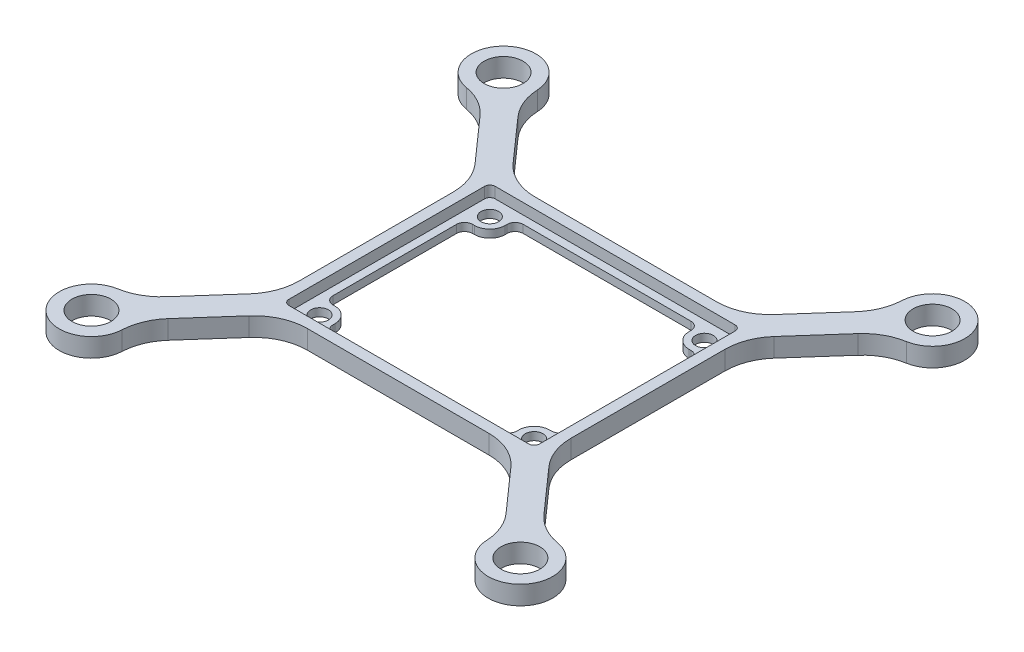
SolidWorks part; units mm, degrees
ref_plane "Front Plane" through (0, 0, 0) normal (0, 0, 1) x (1, 0, 0)
ref_plane "Top Plane" through (0, 0, 0) normal (0, 1, 0) x (1, 0, 0)
ref_plane "Right Plane" through (0, 0, 0) normal (1, 0, 0) x (0, 0, -1)
sketch "Sketch1" plane through (0, 0, 0) normal (0, 1, 0) x (1, 0, 0)
  line L0 (0, 18.7275) -> (0, -18.7275) construction
  line L1 (-22.8525, 18.7275) -> (22.8525, 18.7275) construction
  line L2 (-22.8525, 18.7275) -> (-22.8525, -18.7275) construction
  line L3 (-22.8525, -18.7275) -> (22.8525, -18.7275) construction
  line L4 (22.8525, 18.7275) -> (22.8525, -18.7275) construction
  line L5 (-22.8525, 18.7275) -> (22.8525, -18.7275) construction
  line L6 (-22.8525, -18.7275) -> (22.8525, 18.7275) construction
  line L7 (-22.8525, 0) -> (22.8525, 0) construction
  line L8 (-25.3525, 21.2275) -> (-25.3525, -21.2275)
  line L9 (-25.3525, -21.2275) -> (25.3525, -21.2275)
  line L10 (25.3525, 21.2275) -> (25.3525, -21.2275)
  line L11 (-25.3525, 21.2275) -> (25.3525, 21.2275)
  line L13 (21.8525, 13.0125) -> (21.8525, -13.0125)
  line L15 (-21.8525, 13.0125) -> (-21.8525, -13.0125)
  line L16 (-17.1375, 15.87) -> (-17.1375, 17.7275)
  line L17 (-19.995, 13.0125) -> (-21.8525, 13.0125)
  line L18 (-17.1375, 17.7275) -> (17.1375, 17.7275)
  line L19 (-21.8525, 17.7275) -> (21.8525, 17.7275) construction
  line L20 (-21.8525, 17.7275) -> (-21.8525, -17.7275) construction
  line L21 (19.995, 13.0125) -> (21.8525, 13.0125)
  line L22 (17.1375, 15.87) -> (17.1375, 17.7275)
  line L23 (-17.1375, -15.87) -> (-17.1375, -17.7275)
  line L24 (-19.995, -13.0125) -> (-21.8525, -13.0125)
  line L25 (19.995, -13.0125) -> (21.8525, -13.0125)
  line L26 (17.1375, -15.87) -> (17.1375, -17.7275)
  line L27 (-17.1375, -17.7275) -> (17.1375, -17.7275)
  line L28 (21.8525, 17.7275) -> (21.8525, -17.7275) construction
  line L29 (-21.8525, -17.7275) -> (21.8525, -17.7275) construction
  circle A0 centre (-19.995, 15.87) radius 1.6529
  circle A1 centre (19.995, 15.87) radius 1.6529
  circle A2 centre (19.995, -15.87) radius 1.6529
  circle A3 centre (-19.995, -15.87) radius 1.6529
  arc A5 (-19.995, 13.0125) -> (-17.1375, 15.87) centre (-19.995, 15.87) ccw
  arc A6 (19.995, 13.0125) -> (17.1375, 15.87) centre (19.995, 15.87) cw
  arc A7 (-19.995, -13.0125) -> (-17.1375, -15.87) centre (-19.995, -15.87) cw
  arc A8 (19.995, -13.0125) -> (17.1375, -15.87) centre (19.995, -15.87) ccw
  point P0 (0, 0)
  dimension "D5" = 3.3058
  dimension "D1" = 45.705
  dimension "D2" = 37.455
  dimension "D3" = 2.8575
  dimension "D4" = 2.8575
  dimension "D6" = 2.5
  dimension "D7" = 1
extrude "Boss-Extrude1" add sketch "Sketch1" along normal blind 3.5
sketch "Sketch2" plane through (0, 3.5, 0) normal (0, 1, 0) x (1, 0, 0)
  line L4 (-22.8525, -18.7275) -> (22.8525, -18.7275) construction
  line L5 (22.8525, 18.7275) -> (22.8525, -18.7275) construction
  line L6 (-22.8525, 18.7275) -> (-22.8525, -18.7275) construction
  line L7 (-22.8525, 18.7275) -> (22.8525, 18.7275) construction
  line L16 (-22.8525, -18.7275) -> (22.8525, -18.7275) construction
  line L17 (22.8525, 18.7275) -> (22.8525, -18.7275) construction
  line L18 (-22.8525, 18.7275) -> (-22.8525, -18.7275) construction
  line L19 (-22.8525, 18.7275) -> (22.8525, 18.7275) construction
  line L20 (-23.3525, 19.2275) -> (23.3525, 19.2275)
  line L21 (23.3525, 19.2275) -> (23.3525, -19.2275)
  line L22 (-23.3525, -19.2275) -> (23.3525, -19.2275)
  line L23 (-23.3525, 19.2275) -> (-23.3525, -19.2275)
  dimension "D2" = 0.5
extrude "Cut-Extrude1" cut sketch "Sketch2" against normal blind 2.024
sketch "Sketch3" plane through (0, 3.5, 0) normal (0, 1, 0) x (1, 0, 0)
  line L0 (0, 0) -> (-19.995, 15.87) construction
  line L1 (-19.995, 15.87) -> (-36.3571, 34.3244) construction
  line L2 (0, 21.2275) -> (0, -21.2275) construction
  line L3 (25.3525, 21.2275) -> (-25.3525, 21.2275) construction
  line L4 (-25.3525, -21.2275) -> (25.3525, -21.2275) construction
  line L5 (-18.1244, 17.5285) -> (-34.4865, 35.9829)
  line L6 (-21.8656, 14.2115) -> (-38.2277, 32.6658)
  line L7 (-24.5362, 17.2235) -> (-23.8918, 20.2651)
  line L8 (-23.8918, 20.2651) -> (-20.5507, 20.2651)
  circle A0 centre (-39.9756, 38.4056) radius 6
  circle A1 centre (-39.9756, 38.4056) radius 3.625
  line M8 (25.3525, 21.2275) -> (-25.3525, 21.2275)
  line M9 (-25.3525, 21.2275) -> (-25.3525, -21.2275)
  dimension "D4" = 12
  dimension "D5" = 7.25
  dimension "D1" = 50
  dimension "D6" = 190
  dimension "D2" = 2.5
  dimension "D3" = 2.5
extrude "Boss-Extrude2" add sketch "Sketch3" against normal up to surface (3.5 mm away) contours A0 L6 L5 M9 M8 | L7 L8 L5 L6 M8 M9 | A0 A1 up to face at (19.995, 0, 17.5229)
fillet "Fillet2" radius 1.5 8 edges at (17.1375, 0.738, 17.7275) (21.8525, 0.738, 13.0125) (-17.1375, 0.738, 17.7275) (-21.8525, 0.738, 13.0125) (21.8525, 0.738, -13.0125) (17.1375, 0.738, -17.7275) (-21.8525, 0.738, -13.0125) (-17.1375, 0.738, -17.7275)
fillet "Fillet3" radius 1 4 edges at (-23.3525, 2.488, 19.2275) (23.3525, 2.488, 19.2275) (23.3525, 2.488, -19.2275) (-23.3525, 2.488, -19.2275)
mirror "Mirror1" about plane through (0, 0, 0) normal (0, 0, 1) of "Boss-Extrude2"
mirror "Mirror2" about plane through (0, 0, 0) normal (1, 0, 0) of "Mirror1", "Boss-Extrude2"
fillet "Fillet1" radius 10 16 edges at (-34.4865, 1.75, -35.9829) (-38.2277, 1.75, -32.6658) (-25.3525, 1.75, -18.1442) (-21.404, 1.75, -21.2275) (34.4865, 1.75, 35.9829) (38.2277, 1.75, 32.6658) (25.3525, 1.75, 18.1442) (21.404, 1.75, 21.2275) (38.2277, 1.75, -32.6658) (34.4865, 1.75, -35.9829) (25.3525, 1.75, -18.1442) (21.404, 1.75, -21.2275) (-38.2277, 1.75, 32.6658) (-34.4865, 1.75, 35.9829) (-21.404, 1.75, 21.2275) (-25.3525, 1.75, 18.1442)
